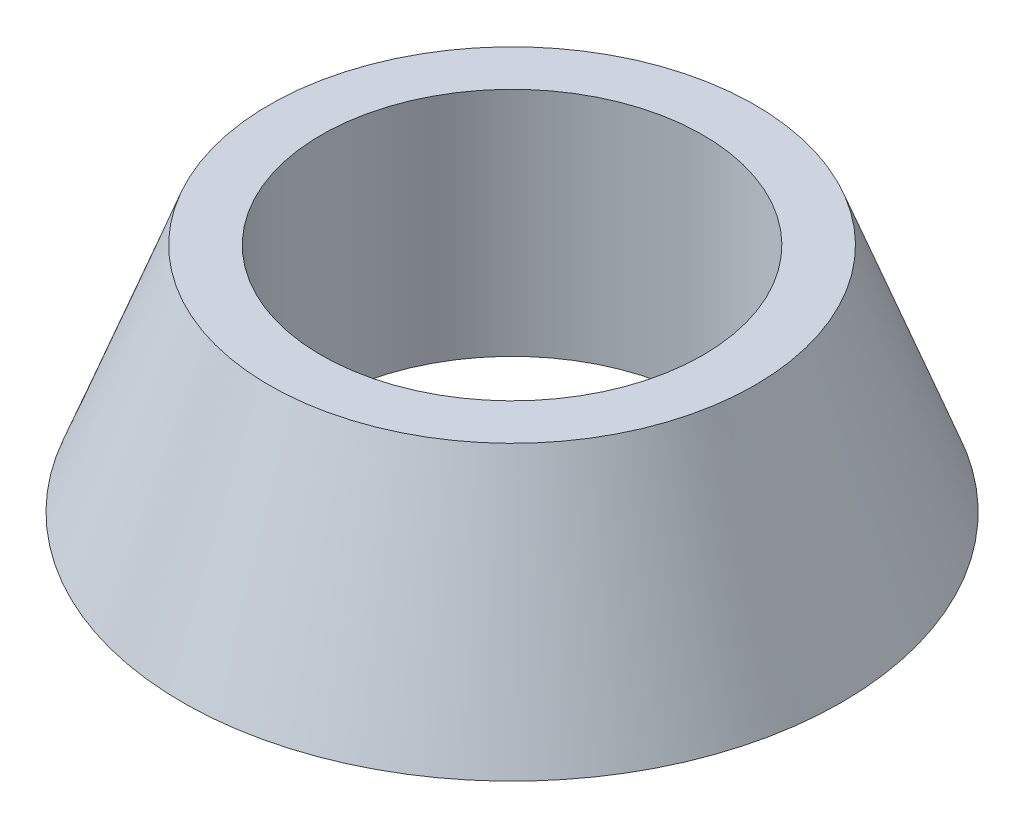
SolidWorks part; units mm, degrees
material "ABS"
ref_plane "Front Plane" through (0, 0, 0) normal (0, 0, 1) x (1, 0, 0)
ref_plane "Top Plane" through (0, 0, 0) normal (0, 1, 0) x (1, 0, 0)
ref_plane "Right Plane" through (0, 0, 0) normal (1, 0, 0) x (0, 0, -1)
sketch "Sketch2" plane through (0, 0, 0) normal (0, 0, 1) x (1, 0, 0)
  line L0 (0, 0) -> (0, 2) construction
  line L1 (0, 2) -> (-1.65, 2) construction
  line L2 (-1.65, 2) -> (-2.1, 2)
  line L3 (-2.1, 2) -> (-2.85, 0)
  line L4 (-2.85, 0) -> (-1.65, 0)
  line L5 (-1.65, 0) -> (-1.65, 2)
  dimension "D1" = 1.2
  dimension "D2" = 0.45
  dimension "D3" = 2
  dimension "D4" = 1.65
revolve "Revolve1" add sketch "Sketch2" angle 360 about L0
